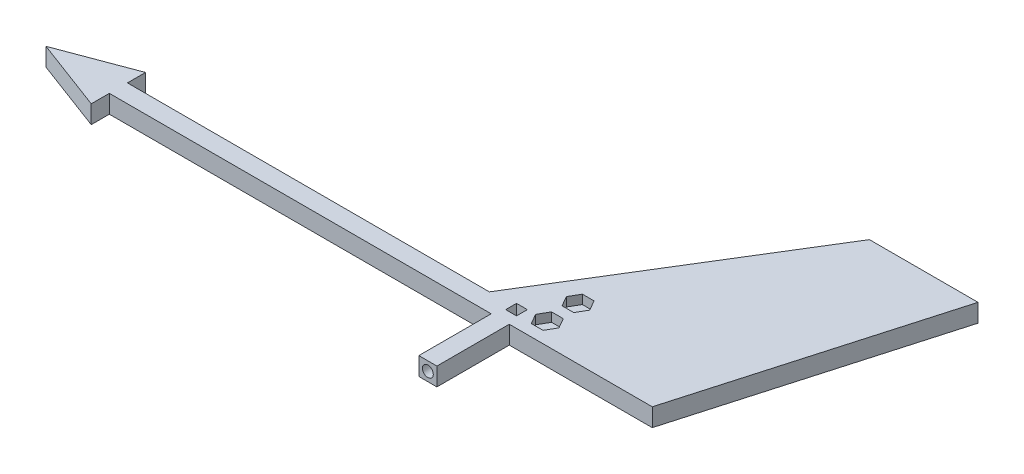
SolidWorks part; units mm, degrees
ref_plane "Front Plane" through (0, 0, 0) normal (0, 0, 1) x (1, 0, 0)
ref_plane "Top Plane" through (0, 0, 0) normal (0, 1, 0) x (1, 0, 0)
ref_plane "Right Plane" through (0, 0, 0) normal (1, 0, 0) x (0, 0, -1)
other "Center of Mass"
sketch "Sketch1" plane through (0, 0, 0) normal (0, 1, 0) x (1, 0, 0)
  line L0 (-20, 0) -> (0, 7.5)
  line L1 (-20, 0) -> (0, -7.5)
  line L2 (0, -7.5) -> (0, 7.5) construction
  line L3 (0, 7.5) -> (0, 2.5)
  line L4 (0, 2.5) -> (100, 2.5)
  line L5 (0, -7.5) -> (0, -2.5)
  line L6 (0, -2.5) -> (150, -2.5)
  line L7 (150, -2.5) -> (170, 67.5)
  line L8 (170, 67.5) -> (140, 67.5)
  line L9 (140, 67.5) -> (100, 2.5)
  point P2 (0, 0)
  dimension "D1" = 150
  dimension "D2" = 100
  dimension "D3" = 70
  dimension "D4" = 20
  dimension "D5" = 40
  dimension "D6" = 20
  dimension "D7" = 15
  dimension "D8" = 5
extrude "Boss-Extrude1" add sketch "Sketch1" along normal mid plane 5
sketch "Sketch2" plane through (0, 2.5, 0) normal (0, 1, 0) x (1, 0, 0)
  line L0 (118.2332, 12) -> (116.6166, 14.8)
  line L2 (116.6166, 14.8) -> (113.3834, 14.8)
  line L5 (113.3834, 9.2) -> (116.6166, 9.2)
  line L6 (116.6166, 9.2) -> (118.2332, 12)
  line L8 (113.3834, 14.8) -> (111.7668, 12)
  line L9 (111.7668, 12) -> (113.3834, 9.2)
  line L12 (0, -2.5) -> (150, -2.5) construction
  line L13 (118.2332, 3.5) -> (116.6166, 6.3)
  line L14 (116.6166, 6.3) -> (113.3834, 6.3)
  line L15 (113.3834, 6.3) -> (111.7668, 3.5)
  line L16 (111.7668, 3.5) -> (113.3834, 0.7)
  line L17 (113.3834, 0.7) -> (116.6166, 0.7)
  line L18 (116.6166, 0.7) -> (118.2332, 3.5)
  line L19 (118.2332, 12) -> (116.6166, 14.8) [skipped]
  line L20 (113.3834, 14.8) -> (111.7668, 12) [skipped]
  line L21 (111.7668, 12) -> (113.3834, 9.2) [skipped]
  circle A0 centre (115, 12) radius 2.8 construction
  circle A1 centre (115, 12) radius 2.8 construction
  circle A2 centre (115, 3.5) radius 2.8 construction
  dimension "D3" = 6
  dimension "D6" = 5.6
  dimension "D5" = 8.5
  dimension "D7" = 15
extrude "Cut-Extrude2" cut sketch "Sketch2" against normal blind 2.5
sketch "Sketch3" plane through (0, 0, 2.5) normal (0, 0, 1) x (1, 0, 0)
  line L1 (105.5, -2.5) -> (110.5, -2.5)
  line L2 (105.5, -2.5) -> (105.5, 2.5)
  line L3 (105.5, 2.5) -> (110.5, 2.5)
  line L4 (110.5, -2.5) -> (110.5, 2.5)
  line L5 (105.5, -2.5) -> (110.5, 2.5) construction
  line L6 (105.5, 2.5) -> (110.5, -2.5) construction
  line L7 (0, 2.5) -> (150, 2.5) construction
  line L8 (0, -2.5) -> (150, -2.5) construction
  point P0 (108, 0)
  point P5 (0, 0)
  point P6 (0, 0)
  point P7 (0, 0)
  point P11 (0, 0)
  point P13 (0, 0)
  point P14 (119.2889, 0)
  point P15 (0, 0)
  point P16 (119.4775, 0)
  dimension "D1" = 5
  dimension "D2" = 108
extrude "Boss-Extrude2" add sketch "Sketch3" along normal blind 20
sketch "Sketch4" plane through (0, 0, 22.5) normal (0, 0, 1) x (1, 0, 0)
  line L0 (105.5, 0) -> (110.5, 0) construction
  line L1 (105.5, 2.5) -> (105.5, -2.5) construction
  line L2 (110.5, -2.5) -> (110.5, 2.5) construction
  circle A0 centre (108, 0) radius 1.5
  point P8 (0, 0)
  dimension "D1" = 3
extrude "Cut-Extrude3" cut sketch "Sketch4" against normal blind 23
sketch "Sketch6" plane through (0, 2.5, 0) normal (0, 1, 0) x (1, 0, 0)
  line L0 (105.5, -2.5) -> (110.5, -2.5) construction
  line L1 (106.5, 0.5) -> (109.5, 0.5)
  line L2 (106.5, 0.5) -> (106.5, 3.5)
  line L3 (106.5, 3.5) -> (109.5, 3.5)
  line L4 (109.5, 0.5) -> (109.5, 3.5)
  line L5 (106.5, 0.5) -> (109.5, 3.5) construction
  line L6 (106.5, 3.5) -> (109.5, 0.5) construction
  point P0 (108, 2)
  point P5 (108, -2.5)
  point P6 (0, 0)
  dimension "D1" = 3
  dimension "D2" = 3
  dimension "D3" = 3
extrude "Cut-Extrude5" cut sketch "Sketch6" against normal blind 4
